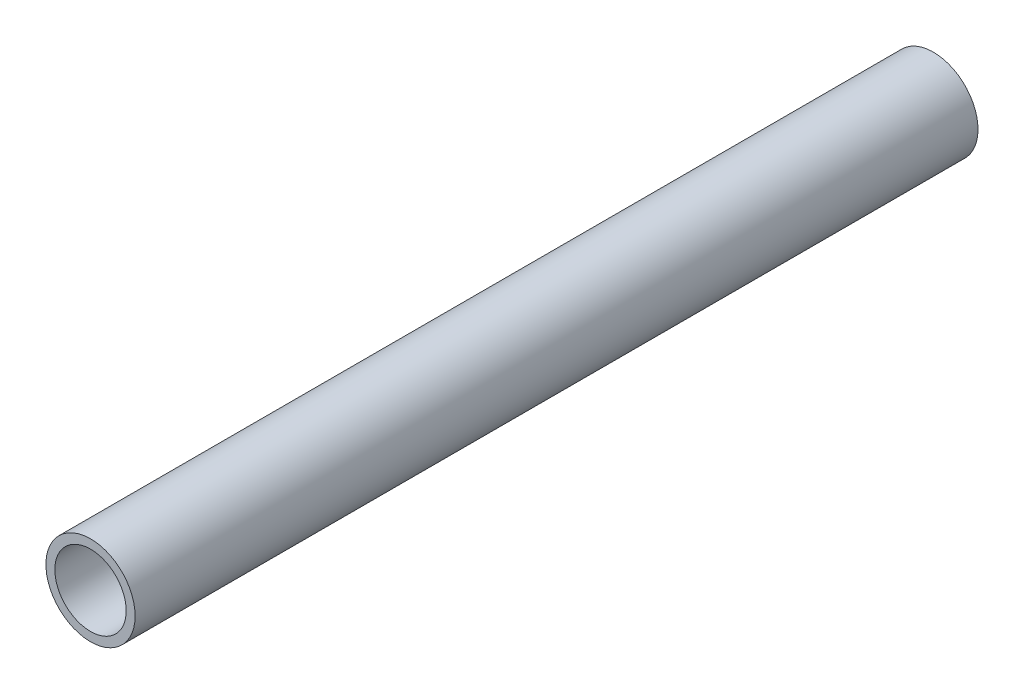
SolidWorks part; units mm, degrees
ref_plane "Plan de face" through (0, 0, 0) normal (0, 0, 1) x (1, 0, 0)
ref_plane "Plan de dessus" through (0, 0, 0) normal (0, 1, 0) x (1, 0, 0)
ref_plane "Plan de droite" through (0, 0, 0) normal (1, 0, 0) x (0, 0, -1)
sketch "Esquisse1" plane through (0, 0, 0) normal (0, 0, 1) x (1, 0, 0)
  circle A0 centre (0, 0) radius 10
  dimension "D1" = 20
extrude "Extru.-Mince1" add sketch "Esquisse1" along normal blind 189 thin thin type one direction reverse wall 2
